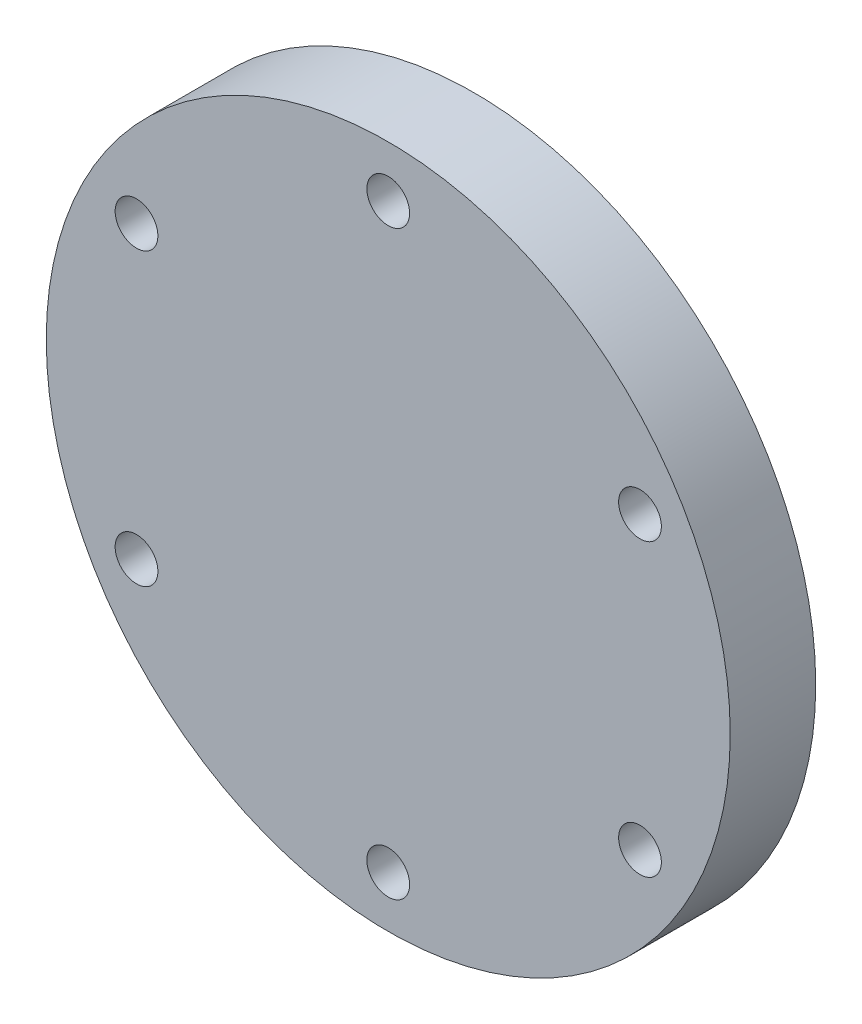
SolidWorks part; units mm, degrees
ref_plane "Front Plane" through (0, 0, 0) normal (0, 0, 1) x (1, 0, 0)
ref_plane "Top Plane" through (0, 0, 0) normal (0, 1, 0) x (1, 0, 0)
ref_plane "Right Plane" through (0, 0, 0) normal (1, 0, 0) x (0, 0, -1)
sketch "Sketch1" plane through (0, 0, 0) normal (0, 0, 1) x (1, 0, 0)
  line L0 (0, 0) -> (0, 17) construction
  circle A0 centre (0, 0) radius 20
  circle A1 centre (0, 0) radius 17 construction
  circle A2 centre (0, 17) radius 1.25
  circle A3 centre (14.7224, 8.5) radius 1.25
  circle A4 centre (14.7224, -8.5) radius 1.25
  circle A5 centre (0, -17) radius 1.25
  circle A6 centre (-14.7224, -8.5) radius 1.25
  circle A7 centre (-14.7224, 8.5) radius 1.25
  point P19 (0, 0)
  dimension "D1" = 34
  dimension "D2" = 40
  dimension "D3" = 2.5
  dimension "D4" = 6
extrude "Boss-Extrude1" add sketch "Sketch1" along normal blind 5
